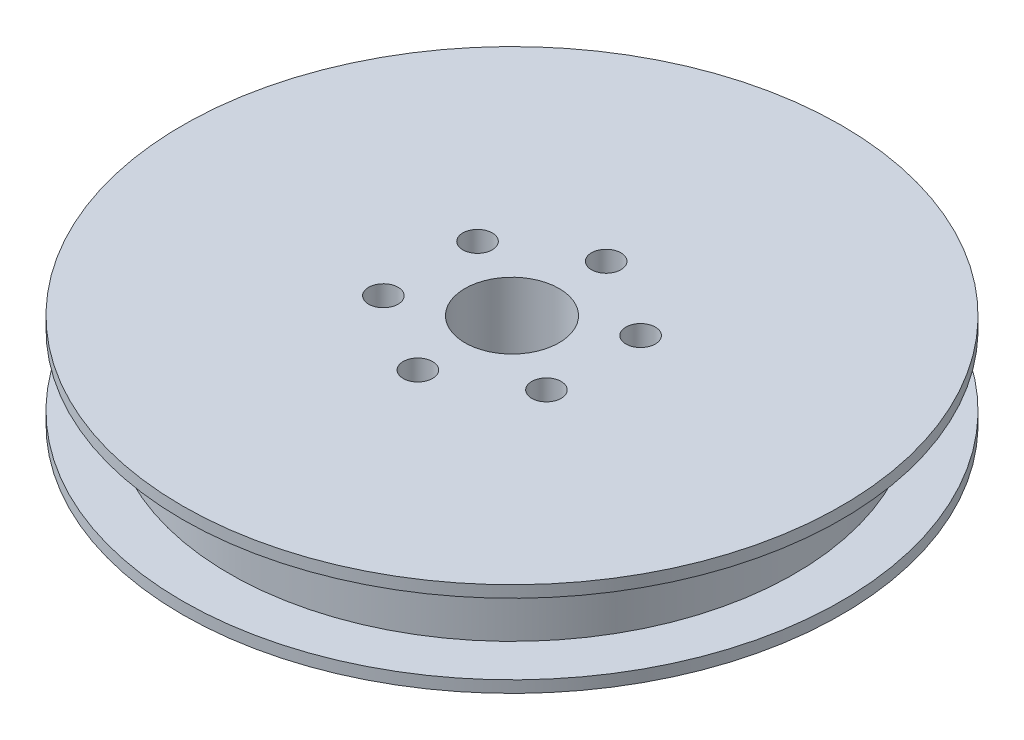
SolidWorks part; units mm, degrees
ref_plane "Front Plane" through (0, 0, 0) normal (0, 0, 1) x (1, 0, 0)
ref_plane "Top Plane" through (0, 0, 0) normal (0, 1, 0) x (1, 0, 0)
ref_plane "Right Plane" through (0, 0, 0) normal (1, 0, 0) x (0, 0, -1)
sketch "Sketch2" plane through (0, 0, 0) normal (0, 1, 0) x (1, 0, 0)
  circle A0 centre (0, 0) radius 76.2
  circle A1 centre (0, 0) radius 25.4
  circle A2 centre (0, 25.4) radius 3.9688
  circle A3 centre (21.997, 12.7) radius 3.9688
  circle A4 centre (21.997, -12.7) radius 3.9688
  circle A5 centre (0, -25.4) radius 3.9688
  circle A6 centre (-21.997, -12.7) radius 3.9688
  circle A7 centre (-21.997, 12.7) radius 3.9688
  circle A8 centre (0, 0) radius 12.7
  point P19 (0, 0)
  dimension "D2" = 152.4
  dimension "D3" = 50.8
  dimension "D4" = 7.9375
  dimension "D5" = 25.4
  dimension "D1" = 6
extrude "Boss-Extrude1" add sketch "Sketch2" along normal blind 19.05 contours A0 A7 A1 A2 A3 A4 A5 A6 | A7 A1 A6 A5 A4 A3 A2
sketch "Sketch3" plane through (0, 19.05, 0) normal (0, 1, 0) x (1, 0, 0)
  circle A0 centre (0, 25.4) radius 3.9688 construction
  circle A1 centre (21.997, 12.7) radius 3.9688 construction
  circle A2 centre (21.997, -12.7) radius 3.9688 construction
  circle A3 centre (0, -25.4) radius 3.9688 construction
  circle A4 centre (-21.997, -12.7) radius 3.9688 construction
  circle A5 centre (0, 0) radius 12.7 construction
  circle A6 centre (-21.997, 12.7) radius 3.9688 construction
  circle A7 centre (0, 25.4) radius 3.9688
  circle A8 centre (21.997, 12.7) radius 3.9688
  circle A9 centre (21.997, -12.7) radius 3.9688
  circle A10 centre (0, -25.4) radius 3.9688
  circle A11 centre (-21.997, -12.7) radius 3.9688
  circle A12 centre (0, 0) radius 12.7
  circle A13 centre (-21.997, 12.7) radius 3.9688
  circle A14 centre (0, 0) radius 88.9
  dimension "D1" = 177.8
extrude "Boss-Extrude2" add sketch "Sketch3" along normal blind 3.175
sketch "Sketch4" plane through (0, 0, 0) normal (0, -1, 0) x (1, 0, 0)
  circle A0 centre (0, 0) radius 12.7 construction
  circle A1 centre (-21.997, -12.7) radius 3.9688 construction
  circle A2 centre (0, -25.4) radius 3.9688 construction
  circle A3 centre (21.997, -12.7) radius 3.9688 construction
  circle A4 centre (21.997, 12.7) radius 3.9688 construction
  circle A5 centre (0, 25.4) radius 3.9688 construction
  circle A6 centre (-21.997, 12.7) radius 3.9688 construction
  circle A7 centre (0, 0) radius 12.7
  circle A8 centre (-21.997, -12.7) radius 3.9688
  circle A9 centre (0, -25.4) radius 3.9688
  circle A10 centre (21.997, -12.7) radius 3.9688
  circle A11 centre (21.997, 12.7) radius 3.9688
  circle A12 centre (0, 25.4) radius 3.9688
  circle A13 centre (-21.997, 12.7) radius 3.9688
  circle A14 centre (0, 0) radius 88.9 construction
  circle A15 centre (0, 0) radius 88.9
extrude "Boss-Extrude3" add sketch "Sketch4" along normal blind 3.175
